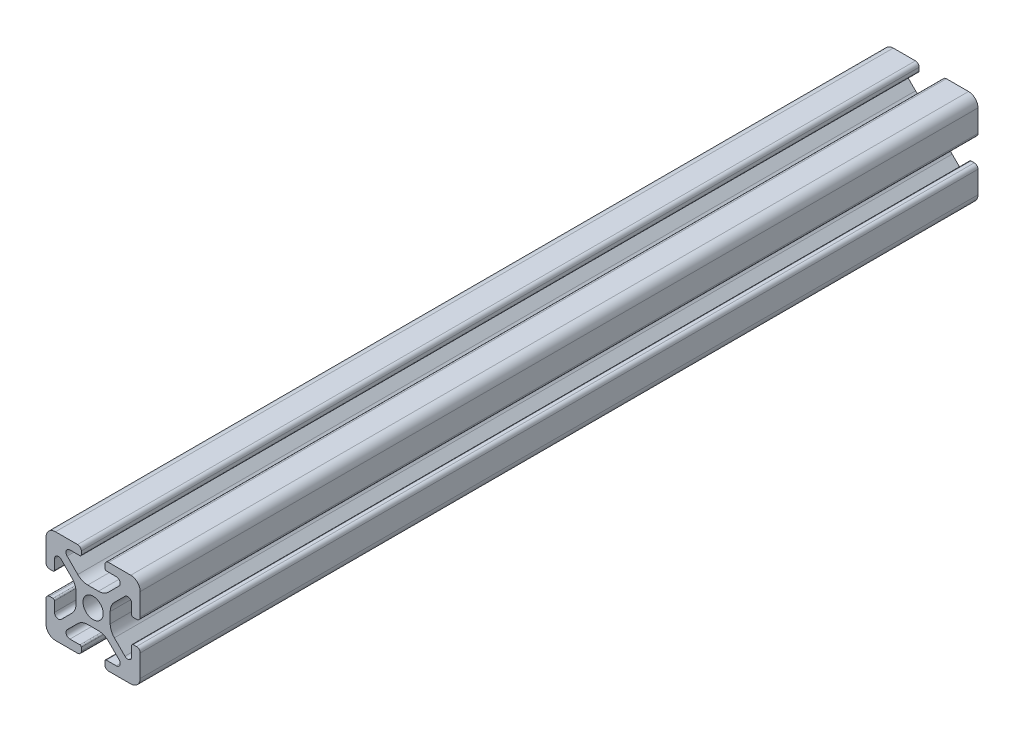
SolidWorks part; units mm, degrees
ref_plane "Front Plane" through (0, 0, 0) normal (0, 0, 1) x (1, 0, 0)
ref_plane "Top Plane" through (0, 0, 0) normal (0, 1, 0) x (1, 0, 0)
ref_plane "Right Plane" through (0, 0, 0) normal (1, 0, 0) x (0, 0, -1)
sketch "Sketch1" plane through (0, 0, 0) normal (0, 0, 1) x (1, 0, 0)
  line L2 (-9.9949, 7.9883) -> (-9.9949, 3.2893)
  line L3 (-7.9883, 9.9949) -> (-3.2893, 9.9949)
  line L4 (-2.5019, 9.2075) -> (-2.5019, 8.4963)
  line L5 (-2.8067, 8.1915) -> (-4.9149, 8.1915)
  line L6 (-5.5076, 6.7606) -> (-3.2528, 4.5058)
  line L7 (-6.7606, 5.5076) -> (-4.5058, 3.2528)
  line L8 (-8.1915, 4.9149) -> (-8.1915, 2.8067)
  line L9 (-8.4963, 2.5019) -> (-9.2075, 2.5019)
  line L11 (-1.1334, 3.6279) -> (1.1334, 3.6279)
  line L12 (-3.6279, 1.1334) -> (-3.6279, -1.1334)
  line L13 (8.4963, 2.5019) -> (9.2075, 2.5019)
  line L14 (8.1915, 4.9149) -> (8.1915, 2.8067)
  line L15 (9.9949, 7.9883) -> (9.9949, 3.2893)
  line L16 (7.9883, 9.9949) -> (3.2893, 9.9949)
  line L17 (2.5019, 9.2075) -> (2.5019, 8.4963)
  line L18 (2.8067, 8.1915) -> (4.9149, 8.1915)
  line L19 (3.6279, 1.1334) -> (3.6279, -1.1334)
  line L20 (5.5076, 6.7606) -> (3.2528, 4.5058)
  line L21 (6.7606, 5.5076) -> (4.5058, 3.2528)
  line L22 (-8.4963, -2.5019) -> (-9.2075, -2.5019)
  line L23 (-8.1915, -4.9149) -> (-8.1915, -2.8067)
  line L24 (-6.7606, -5.5076) -> (-4.5058, -3.2528)
  line L25 (-5.5076, -6.7606) -> (-3.2528, -4.5058)
  line L26 (-2.8067, -8.1915) -> (-4.9149, -8.1915)
  line L27 (-2.5019, -9.2075) -> (-2.5019, -8.4963)
  line L28 (-7.9883, -9.9949) -> (-3.2893, -9.9949)
  line L29 (-9.9949, -7.9883) -> (-9.9949, -3.2893)
  line L30 (9.9949, -7.9883) -> (9.9949, -3.2893)
  line L31 (7.9883, -9.9949) -> (3.2893, -9.9949)
  line L32 (2.5019, -9.2075) -> (2.5019, -8.4963)
  line L33 (2.8067, -8.1915) -> (4.9149, -8.1915)
  line L34 (5.5076, -6.7606) -> (3.2528, -4.5058)
  line L35 (6.7606, -5.5076) -> (4.5058, -3.2528)
  line L36 (8.1915, -4.9149) -> (8.1915, -2.8067)
  line L37 (8.4963, -2.5019) -> (9.2075, -2.5019)
  line L38 (-1.1334, -3.6279) -> (1.1334, -3.6279)
  circle A0 centre (0, 0) radius 2.1463
  arc A1 (-9.9949, 7.9883) -> (-7.9883, 9.9949) centre (-7.9883, 7.9883) cw
  arc A2 (-6.7606, 5.5076) -> (-8.1915, 4.9149) centre (-7.3533, 4.9149) ccw
  arc A3 (-4.9149, 8.1915) -> (-5.5076, 6.7606) centre (-4.9149, 7.3533) ccw
  arc A4 (-3.2893, 9.9949) -> (-2.5019, 9.2075) centre (-3.2893, 9.2075) cw
  arc A5 (-9.9949, 3.2893) -> (-9.2075, 2.5019) centre (-9.2075, 3.2893) ccw
  arc A6 (-8.1915, 2.8067) -> (-8.4963, 2.5019) centre (-8.4963, 2.8067) cw
  arc A7 (-2.5019, 8.4963) -> (-2.8067, 8.1915) centre (-2.8067, 8.4963) cw
  arc A8 (-1.1334, 3.6279) -> (-3.2528, 4.5058) centre (-1.1334, 6.6251) cw
  arc A9 (-3.6279, 1.1334) -> (-4.5058, 3.2528) centre (-6.6251, 1.1334) ccw
  arc A10 (8.1915, 2.8067) -> (8.4963, 2.5019) centre (8.4963, 2.8067) ccw
  arc A11 (9.9949, 3.2893) -> (9.2075, 2.5019) centre (9.2075, 3.2893) cw
  arc A12 (9.9949, 7.9883) -> (7.9883, 9.9949) centre (7.9883, 7.9883) ccw
  arc A13 (3.2893, 9.9949) -> (2.5019, 9.2075) centre (3.2893, 9.2075) ccw
  arc A14 (2.5019, 8.4963) -> (2.8067, 8.1915) centre (2.8067, 8.4963) ccw
  arc A15 (1.1334, 3.6279) -> (3.2528, 4.5058) centre (1.1334, 6.6251) ccw
  arc A16 (3.6279, 1.1334) -> (4.5058, 3.2528) centre (6.6251, 1.1334) cw
  arc A17 (6.7606, 5.5076) -> (8.1915, 4.9149) centre (7.3533, 4.9149) cw
  arc A18 (4.9149, 8.1915) -> (5.5076, 6.7606) centre (4.9149, 7.3533) cw
  arc A19 (-3.6279, -1.1334) -> (-4.5058, -3.2528) centre (-6.6251, -1.1334) cw
  arc A20 (-1.1334, -3.6279) -> (-3.2528, -4.5058) centre (-1.1334, -6.6251) ccw
  arc A21 (-2.5019, -8.4963) -> (-2.8067, -8.1915) centre (-2.8067, -8.4963) ccw
  arc A22 (-8.1915, -2.8067) -> (-8.4963, -2.5019) centre (-8.4963, -2.8067) ccw
  arc A23 (-9.9949, -3.2893) -> (-9.2075, -2.5019) centre (-9.2075, -3.2893) cw
  arc A24 (-3.2893, -9.9949) -> (-2.5019, -9.2075) centre (-3.2893, -9.2075) ccw
  arc A25 (-4.9149, -8.1915) -> (-5.5076, -6.7606) centre (-4.9149, -7.3533) cw
  arc A26 (-6.7606, -5.5076) -> (-8.1915, -4.9149) centre (-7.3533, -4.9149) cw
  arc A27 (-9.9949, -7.9883) -> (-7.9883, -9.9949) centre (-7.9883, -7.9883) ccw
  arc A28 (9.9949, -7.9883) -> (7.9883, -9.9949) centre (7.9883, -7.9883) cw
  arc A29 (6.7606, -5.5076) -> (8.1915, -4.9149) centre (7.3533, -4.9149) ccw
  arc A30 (4.9149, -8.1915) -> (5.5076, -6.7606) centre (4.9149, -7.3533) ccw
  arc A31 (3.2893, -9.9949) -> (2.5019, -9.2075) centre (3.2893, -9.2075) cw
  arc A32 (9.9949, -3.2893) -> (9.2075, -2.5019) centre (9.2075, -3.2893) ccw
  arc A33 (8.1915, -2.8067) -> (8.4963, -2.5019) centre (8.4963, -2.8067) cw
  arc A34 (2.5019, -8.4963) -> (2.8067, -8.1915) centre (2.8067, -8.4963) cw
  arc A35 (1.1334, -3.6279) -> (3.2528, -4.5058) centre (1.1334, -6.6251) cw
  arc A36 (3.6279, -1.1334) -> (4.5058, -3.2528) centre (6.6251, -1.1334) ccw
extrude "Boss-Extrude1" add sketch "Sketch1" along normal mid plane 177.8
